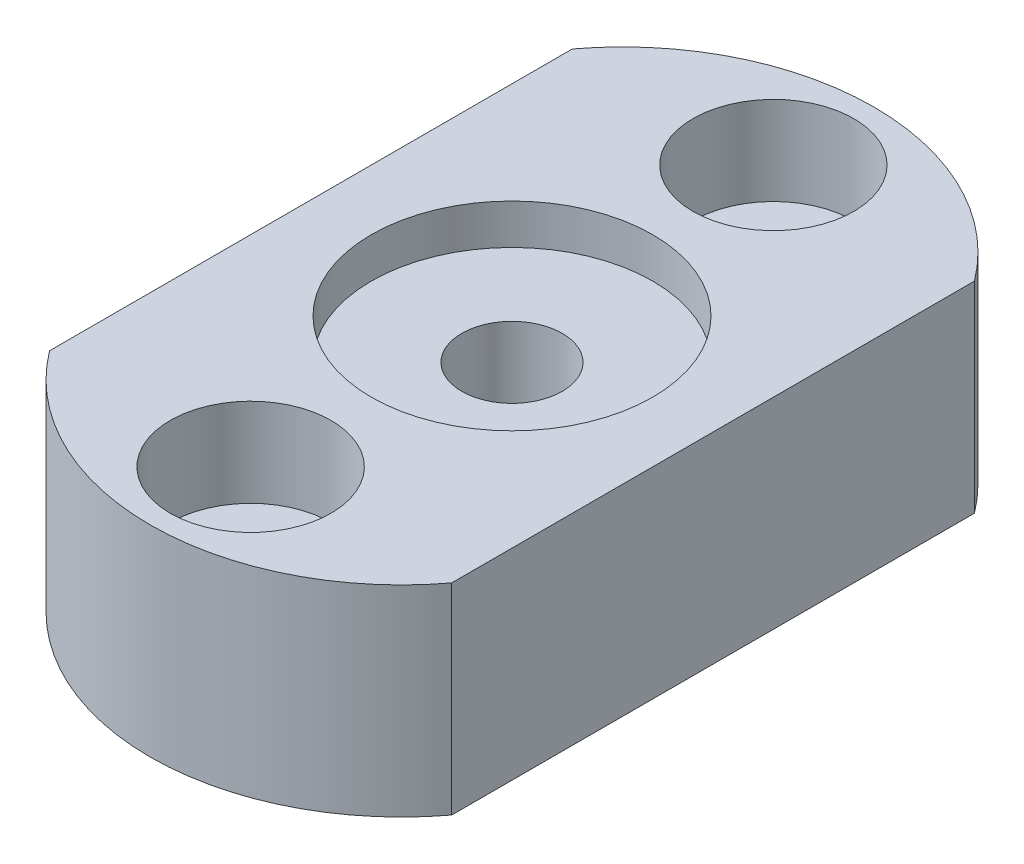
SolidWorks part; units mm, degrees
ref_plane "前视基准面" through (0, 0, 0) normal (0, 0, 1) x (1, 0, 0)
ref_plane "上视基准面" through (0, 0, 0) normal (0, 1, 0) x (1, 0, 0)
ref_plane "右视基准面" through (0, 0, 0) normal (1, 0, 0) x (0, 0, -1)
other "Configuration Table"
sketch "Sketch1" plane through (0, 0, 0) normal (0, 1, 0) x (1, 0, 0)
  line L1 (-10, 13) -> (10, 13) construction
  line L2 (-10, 13) -> (-10, -13)
  line L3 (-10, -13) -> (10, -13) construction
  line L4 (10, 13) -> (10, -13)
  line L5 (-10, 13) -> (10, -13) construction
  line L6 (-10, -13) -> (10, 13) construction
  arc A0 (-10, 13) -> (10, 13) centre (0, 5.5) cw
  arc A1 (10, -13) -> (-10, -13) centre (0, -5.5) cw
  point P0 (0, 0)
  point P6 (0, 13)
  point P7 (0, 18)
  point P8 (0, -13)
  point P9 (0, -18)
  dimension "D1" = 5
  dimension "D2" = 5
extrude "Boss-Extrude1" add sketch "Sketch1" along normal blind 10
sketch "Sketch2" plane through (0, 10, 0) normal (0, 1, 0) x (1, 0, 0)
  circle A0 centre (0, 13) radius 4
  circle A1 centre (0, -13) radius 4
extrude "Cut-Extrude1" cut sketch "Sketch2" against normal blind 4.4
sketch "Sketch3" plane through (0, 5.6, 0) normal (0, 1, 0) x (1, 0, 0)
  circle A0 centre (0, 13) radius 2.15
  circle A1 centre (0, -13) radius 2.15
extrude "Cut-Extrude2" cut sketch "Sketch3" against normal up to next
sketch "Sketch4" plane through (0, 10, 0) normal (0, 1, 0) x (1, 0, 0)
  circle A0 centre (0, 0) radius 7
extrude "Cut-Extrude3" cut sketch "Sketch4" against normal blind 2
sketch "Sketch5" plane through (0, 8, 0) normal (0, 1, 0) x (1, 0, 0)
  circle A0 centre (0, 0) radius 2.5
extrude "Cut-Extrude4" cut sketch "Sketch5" against normal up to next
sketch "Sketch6" plane through (0, 0, 0) normal (0, -1, 0) x (1, 0, 0)
  circle A0 centre (0, 0) radius 7
extrude "Cut-Extrude5" cut sketch "Sketch6" against normal blind 2
